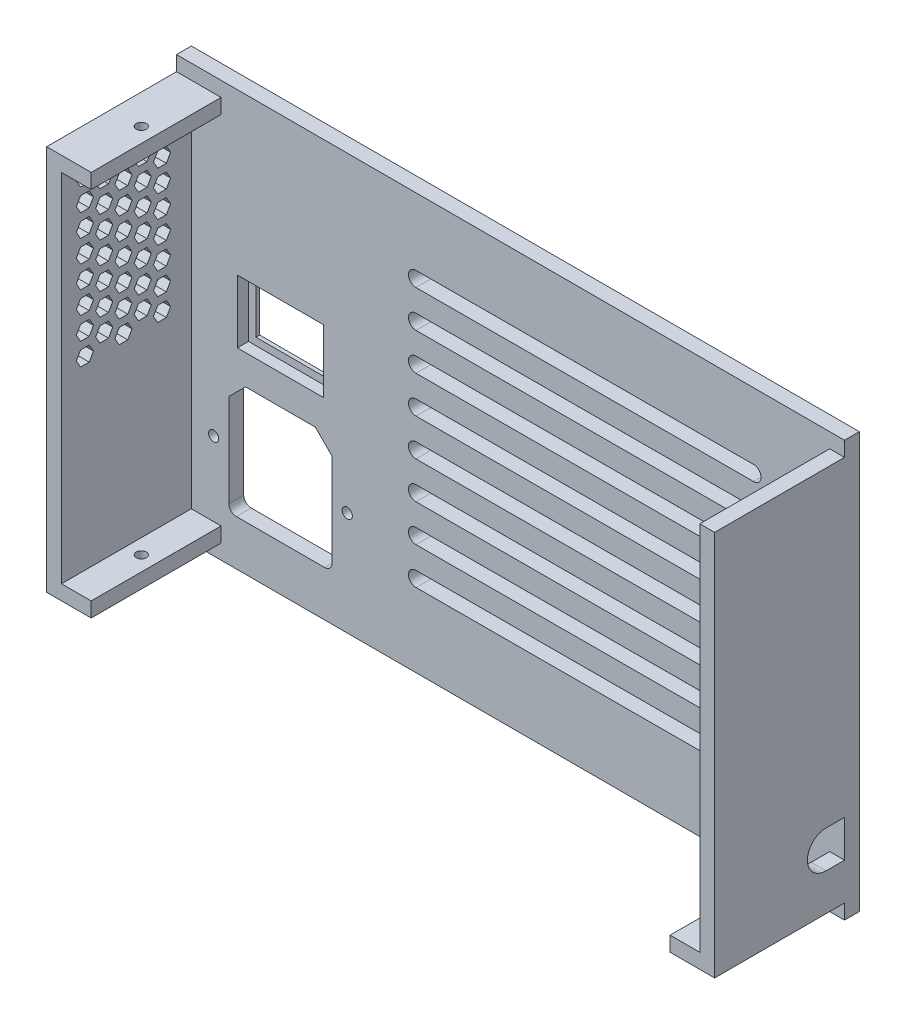
SolidWorks part; units mm, degrees
material "PET"
ref_plane "Přední rovina" through (0, 0, 0) normal (0, 0, 1) x (1, 0, 0)
ref_plane "Horní rovina" through (0, 0, 0) normal (0, 1, 0) x (1, 0, 0)
ref_plane "Pravá rovina" through (0, 0, 0) normal (1, 0, 0) x (0, 0, -1)
sketch "Skica1" plane through (0, 0, 0) normal (0, 0, 1) x (1, 0, 0)
  line L1 (-90, -56) -> (90, -56)
  line L2 (-90, -56) -> (-90, 56)
  line L3 (-90, 56) -> (90, 56)
  line L4 (90, -56) -> (90, 56)
  line L5 (-90, -56) -> (90, 56) construction
  line L6 (-90, 56) -> (90, -56) construction
  point P0 (0, 0)
  dimension "D1" = 112
  dimension "D2" = 180
extrude "Přidat vysunutím1" add sketch "Skica1" along normal blind 4
sketch "Skica2" plane through (0, 0, 4) normal (0, 0, 1) x (1, 0, 0)
  line L0 (-90, 0) -> (90, 0) construction
  line L1 (-90, 56) -> (-90, -56) construction
  line L2 (90, -56) -> (90, 56) construction
  line L3 (90, 56) -> (-90, 56) construction
  line L4 (-90, 52) -> (-86, 52)
  line L5 (-90, 52) -> (-90, -52)
  line L6 (-90, -52) -> (-86, -52)
  line L7 (-86, 52) -> (-86, -52)
  line L8 (-90, 52) -> (-86, -52) construction
  line L9 (-90, -52) -> (-86, 52) construction
  line L10 (-90, -56) -> (90, -56) construction
  line L11 (0, 56) -> (0, -56) construction
  line L12 (90, -52) -> (86, 52) construction
  line L13 (90, 52) -> (86, -52) construction
  line L14 (86, 52) -> (86, -52)
  line L15 (90, -52) -> (86, -52)
  line L16 (90, 52) -> (90, -52)
  line L17 (90, 52) -> (86, 52)
  point P10 (-88, 0)
  point P21 (88, 0)
  dimension "D1" = 4
  dimension "D2" = 4
  dimension "D3" = 4
extrude "Přidat vysunutím2" add sketch "Skica2" along normal blind 35
sketch "Skica3" plane through (0, 0, 4) normal (0, 0, 1) x (1, 0, 0)
  line L5 (-86, 52) -> (-78, 52)
  line L6 (-86, 52) -> (-86, 48)
  line L7 (86, -52) -> (78, -52)
  line L8 (86, -52) -> (86, -48)
  line L9 (86, -48) -> (78, -48)
  line L10 (78, -52) -> (78, -48)
  line L11 (86, -52) -> (78, -48) construction
  line L12 (86, -48) -> (78, -52) construction
  line L13 (-86, -52) -> (-78, -52)
  line L14 (-86, -52) -> (-86, -48)
  line L15 (-86, -48) -> (-78, -48)
  line L16 (-78, -52) -> (-78, -48)
  line L17 (-86, -52) -> (-78, -48) construction
  line L18 (-86, -48) -> (-78, -52) construction
  line L19 (-86, 48) -> (-78, 48)
  line L20 (-78, 52) -> (-78, 48)
  line L21 (-86, 52) -> (-78, 48) construction
  line L22 (-86, 48) -> (-78, 52) construction
  point P4 (-82, 50)
  point P10 (82, -50)
  point P16 (-82, -50)
  dimension "D1" = 4
  dimension "D2" = 8
  dimension "D3" = 4
  dimension "D4" = 8
  dimension "D5" = 4
  dimension "D6" = 8
extrude "Přidat vysunutím3" add sketch "Skica3" along normal up to surface (35 mm away) up to face at (-88, 0, 39)
sketch "Skica5" plane through (0, 52, 0) normal (0, 1, 0) x (1, 0, 0)
  line L0 (-82, -21.5) -> (-78, -21.5) construction
  line L1 (-78, -39) -> (-78, -4) construction
  line L2 (0, 0) -> (0, -47.5141) construction
  line L3 (90, 0) -> (-90, 0) construction
  line L4 (82, -21.5) -> (78, -21.5) construction
  circle A0 centre (-82, -21.5) radius 1.35
  circle A1 centre (82, -21.5) radius 1.35
  dimension "D1" = 2.7
  dimension "D2" = 4
extrude "Odebrat vysunutím2" cut sketch "Skica5" against normal up to surface (104 mm away) up to face at (-84, -52, 21.5)
sketch "Skica8" plane through (86, 0, 0) normal (-1, 0, 0) x (0, 0, 1)
  line L0 (4, 52) -> (4, -48) construction
  line L1 (39, -52) -> (4, -52) construction
  line L2 (9, -42) -> (4, -42)
  line L3 (4, -42) -> (4, -32)
  line L4 (4, -32) -> (9, -32)
  arc A0 (9, -42) -> (9, -32) centre (9, -37) ccw
  dimension "D1" = 10
  dimension "D2" = 15
extrude "Odebrat vysunutím4" cut sketch "Skica8" against normal up to surface (4 mm away) up to face at (90, 0, 11.75)
sketch "Skica9" plane through (0, 0, 4) normal (0, 0, 1) x (1, 0, 0)
  line L0 (20, -34) -> (20, 36) construction
  line L1 (90, 56) -> (-90, 56) construction
  line L3 (-25.4999, 35.8936) -> (65.4999, 36.1064) construction
  line L4 (-25.5046, 37.8936) -> (65.4952, 38.1064)
  line L5 (-25.4952, 33.8936) -> (65.5046, 34.1064)
  line L6 (-25.4999, 25.8936) -> (65.4999, 26.1064) construction
  line L7 (-25.5046, 27.8936) -> (65.4952, 28.1064)
  line L8 (-25.4952, 23.8936) -> (65.5046, 24.1064)
  line L9 (-25.4999, 15.8936) -> (65.4999, 16.1064) construction
  line L10 (-25.5046, 17.8936) -> (65.4952, 18.1064)
  line L11 (-25.4952, 13.8936) -> (65.5046, 14.1064)
  line L12 (-25.4999, 5.8936) -> (65.4999, 6.1064) construction
  line L13 (-25.5046, 7.8936) -> (65.4952, 8.1064)
  line L14 (-25.4952, 3.8936) -> (65.5046, 4.1064)
  line L15 (-25.4999, -4.1064) -> (65.4999, -3.8936) construction
  line L16 (-25.5046, -2.1064) -> (65.4952, -1.8936)
  line L17 (-25.4952, -6.1064) -> (65.5046, -5.8936)
  line L18 (-25.4999, -14.1064) -> (65.4999, -13.8936) construction
  line L19 (-25.5046, -12.1064) -> (65.4952, -11.8936)
  line L20 (-25.4952, -16.1064) -> (65.5046, -15.8936)
  line L21 (-25.4999, -24.1064) -> (65.4999, -23.8936) construction
  line L22 (-25.5046, -22.1064) -> (65.4952, -21.8936)
  line L23 (-25.4952, -26.1064) -> (65.5046, -25.8936)
  line L24 (-25.4999, -34.1064) -> (65.4999, -33.8936) construction
  line L25 (-25.5046, -32.1064) -> (65.4952, -31.8936)
  line L26 (-25.4952, -36.1064) -> (65.5046, -35.8936)
  line L28 (90, -52) -> (90, 52) construction
  arc A0 (-25.5046, 37.8936) -> (-25.4952, 33.8936) centre (-25.4999, 35.8936) ccw
  arc A1 (65.5046, 34.1064) -> (65.4952, 38.1064) centre (65.4999, 36.1064) ccw
  arc A2 (-25.5046, 27.8936) -> (-25.4952, 23.8936) centre (-25.4999, 25.8936) ccw
  arc A3 (65.5046, 24.1064) -> (65.4952, 28.1064) centre (65.4999, 26.1064) ccw
  arc A4 (-25.5046, 17.8936) -> (-25.4952, 13.8936) centre (-25.4999, 15.8936) ccw
  arc A5 (65.5046, 14.1064) -> (65.4952, 18.1064) centre (65.4999, 16.1064) ccw
  arc A6 (-25.5046, 7.8936) -> (-25.4952, 3.8936) centre (-25.4999, 5.8936) ccw
  arc A7 (65.5046, 4.1064) -> (65.4952, 8.1064) centre (65.4999, 6.1064) ccw
  arc A8 (-25.5046, -2.1064) -> (-25.4952, -6.1064) centre (-25.4999, -4.1064) ccw
  arc A9 (65.5046, -5.8936) -> (65.4952, -1.8936) centre (65.4999, -3.8936) ccw
  arc A10 (-25.5046, -12.1064) -> (-25.4952, -16.1064) centre (-25.4999, -14.1064) ccw
  arc A11 (65.5046, -15.8936) -> (65.4952, -11.8936) centre (65.4999, -13.8936) ccw
  arc A12 (-25.5046, -22.1064) -> (-25.4952, -26.1064) centre (-25.4999, -24.1064) ccw
  arc A13 (65.5046, -25.8936) -> (65.4952, -21.8936) centre (65.4999, -23.8936) ccw
  arc A14 (-25.5046, -32.1064) -> (-25.4952, -36.1064) centre (-25.4999, -34.1064) ccw
  arc A15 (65.5046, -35.8936) -> (65.4952, -31.8936) centre (65.4999, -33.8936) ccw
  point P8 (20, 36)
  point P17 (20, 26)
  point P24 (20, 16)
  point P31 (20, 6)
  point P38 (20, -4)
  point P45 (20, -14)
  point P52 (20, -24)
  point P59 (20, -34)
  dimension "D2" = 95
  dimension "D1" = 4
  dimension "D3" = 20
  dimension "D5" = 70
  dimension "D4" = 8
extrude "Odebrat vysunutím5" cut sketch "Skica9" against normal up to surface (4 mm away) up to face at (0, 0, 0)
sketch "Skica12" plane through (-90, 0, 0) normal (-1, 0, 0) x (0, 0, 1)
  line L0 (21.5, 52) -> (21.5, -52) construction
  line L1 (39, 52) -> (4, 52) construction
  line L2 (39, -52) -> (4, -52) construction
  line L3 (11.9737, 33.5) -> (31.0263, 44.5) construction
  line L4 (11.2237, 34.799) -> (30.2763, 45.799)
  line L5 (12.7237, 32.201) -> (31.7763, 43.201)
  line L6 (11.9737, 26.5) -> (31.0263, 37.5) construction
  line L7 (11.2237, 27.799) -> (30.2763, 38.799)
  line L8 (12.7237, 25.201) -> (31.7763, 36.201)
  line L9 (11.9737, 19.5) -> (31.0263, 30.5) construction
  line L10 (11.2237, 20.799) -> (30.2763, 31.799)
  line L11 (12.7237, 18.201) -> (31.7763, 29.201)
  line L12 (11.9737, 12.5) -> (31.0263, 23.5) construction
  line L13 (11.2237, 13.799) -> (30.2763, 24.799)
  line L14 (12.7237, 11.201) -> (31.7763, 22.201)
  line L15 (11.9737, 5.5) -> (31.0263, 16.5) construction
  line L16 (11.2237, 6.799) -> (30.2763, 17.799)
  line L17 (12.7237, 4.201) -> (31.7763, 15.201)
  line L18 (11.9737, -1.5) -> (31.0263, 9.5) construction
  line L19 (11.2237, -0.201) -> (30.2763, 10.799)
  line L20 (12.7237, -2.799) -> (31.7763, 8.201)
  line L21 (-9.8311, 46) -> (42.9995, 46) construction
  line L25 (10.4737, 58.4395) -> (10.4737, -1.4392) construction
  arc A0 (11.2237, 34.799) -> (12.7237, 32.201) centre (11.9737, 33.5) ccw
  arc A1 (31.7763, 43.201) -> (30.2763, 45.799) centre (31.0263, 44.5) ccw
  arc A2 (11.2237, 27.799) -> (12.7237, 25.201) centre (11.9737, 26.5) ccw
  arc A3 (31.7763, 36.201) -> (30.2763, 38.799) centre (31.0263, 37.5) ccw
  arc A4 (11.2237, 20.799) -> (12.7237, 18.201) centre (11.9737, 19.5) ccw
  arc A5 (31.7763, 29.201) -> (30.2763, 31.799) centre (31.0263, 30.5) ccw
  arc A6 (11.2237, 13.799) -> (12.7237, 11.201) centre (11.9737, 12.5) ccw
  arc A7 (31.7763, 22.201) -> (30.2763, 24.799) centre (31.0263, 23.5) ccw
  arc A8 (11.2237, 6.799) -> (12.7237, 4.201) centre (11.9737, 5.5) ccw
  arc A9 (31.7763, 15.201) -> (30.2763, 17.799) centre (31.0263, 16.5) ccw
  arc A10 (11.2237, -0.201) -> (12.7237, -2.799) centre (11.9737, -1.5) ccw
  arc A11 (31.7763, 8.201) -> (30.2763, 10.799) centre (31.0263, 9.5) ccw
  point P8 (21.5, 39)
  point P17 (21.5, 32)
  point P24 (21.5, 25)
  point P31 (21.5, 18)
  point P38 (21.5, 11)
  point P45 (21.5, 4)
  dimension "D2" = 25
  dimension "D4" = 6
  dimension "D1" = 3
  dimension "D3" = 60
  dimension "D5" = 6
sketch "Skica13" plane through (-90, 0, 0) normal (-1, 0, 0) x (0, 0, 1)
  line L0 (39, 52) -> (4, 52) construction
  line L1 (35, 46) -> (8, 46) construction
  line L2 (35, 46) -> (35, 1.7121) construction
  line L3 (35, 1.7121) -> (8, 1.7121) construction
  line L4 (8, 46) -> (8, 1.7121) construction
  line L5 (35, 46) -> (8, 1.7121) construction
  line L6 (35, 1.7121) -> (8, 46) construction
  line L7 (39, 52) -> (39, -52) construction
  line L8 (4, 56) -> (4, 52) construction
  line L9 (32.6906, 44) -> (27.4944, 41) construction
  line L10 (35, 44) -> (33.8453, 46)
  line L11 (33.8453, 46) -> (31.5359, 46)
  line L12 (31.5359, 46) -> (30.3812, 44)
  line L13 (30.3812, 44) -> (31.5359, 42)
  line L14 (31.5359, 42) -> (33.8453, 42)
  line L15 (33.8453, 42) -> (35, 44)
  line L16 (29.8038, 41) -> (28.6491, 43)
  line L17 (28.6491, 43) -> (26.3397, 43)
  line L18 (26.3397, 43) -> (25.185, 41)
  line L19 (25.185, 41) -> (26.3397, 39)
  line L20 (26.3397, 39) -> (28.6491, 39)
  line L21 (28.6491, 39) -> (29.8038, 41)
  line L22 (35, 32) -> (33.8453, 34)
  line L23 (35, 38) -> (33.8453, 40)
  line L24 (33.8453, 40) -> (31.5359, 40)
  line L25 (31.5359, 40) -> (30.3812, 38)
  line L26 (30.3812, 38) -> (31.5359, 36)
  line L27 (31.5359, 36) -> (33.8453, 36)
  line L28 (33.8453, 36) -> (35, 38)
  line L29 (29.8038, 35) -> (28.6491, 37)
  line L30 (28.6491, 37) -> (26.3397, 37)
  line L31 (26.3397, 37) -> (25.185, 35)
  line L32 (25.185, 35) -> (26.3397, 33)
  line L33 (26.3397, 33) -> (28.6491, 33)
  line L34 (28.6491, 33) -> (29.8038, 35)
  line L35 (33.8453, 34) -> (31.5359, 34)
  line L36 (31.5359, 34) -> (30.3812, 32)
  line L37 (30.3812, 32) -> (31.5359, 30)
  line L38 (31.5359, 30) -> (33.8453, 30)
  line L39 (33.8453, 30) -> (35, 32)
  line L40 (35, 26) -> (33.8453, 28)
  line L41 (33.8453, 28) -> (31.5359, 28)
  line L42 (31.5359, 28) -> (30.3812, 26)
  line L43 (30.3812, 26) -> (31.5359, 24)
  line L44 (31.5359, 24) -> (33.8453, 24)
  line L45 (33.8453, 24) -> (35, 26)
  line L46 (29.8038, 29) -> (28.6491, 31)
  line L47 (28.6491, 31) -> (26.3397, 31)
  line L48 (26.3397, 31) -> (25.185, 29)
  line L49 (25.185, 29) -> (26.3397, 27)
  line L50 (26.3397, 27) -> (28.6491, 27)
  line L51 (28.6491, 27) -> (29.8038, 29)
  line L52 (29.8038, 23) -> (28.6491, 25)
  line L53 (28.6491, 25) -> (26.3397, 25)
  line L54 (26.3397, 25) -> (25.185, 23)
  line L55 (25.185, 23) -> (26.3397, 21)
  line L56 (26.3397, 21) -> (28.6491, 21)
  line L57 (28.6491, 21) -> (29.8038, 23)
  line L58 (35, 20) -> (33.8453, 22)
  line L59 (33.8453, 22) -> (31.5359, 22)
  line L60 (31.5359, 22) -> (30.3812, 20)
  line L61 (30.3812, 20) -> (31.5359, 18)
  line L62 (31.5359, 18) -> (33.8453, 18)
  line L63 (33.8453, 18) -> (35, 20)
  line L64 (35, 14) -> (33.8453, 16)
  line L65 (33.8453, 16) -> (31.5359, 16)
  line L66 (31.5359, 16) -> (30.3812, 14)
  line L67 (30.3812, 14) -> (31.5359, 12)
  line L68 (31.5359, 12) -> (33.8453, 12)
  line L69 (33.8453, 12) -> (35, 14)
  line L70 (29.8038, 17) -> (28.6491, 19)
  line L71 (28.6491, 19) -> (26.3397, 19)
  line L72 (26.3397, 19) -> (25.185, 17)
  line L73 (25.185, 17) -> (26.3397, 15)
  line L74 (26.3397, 15) -> (28.6491, 15)
  line L75 (28.6491, 15) -> (29.8038, 17)
  line L76 (29.8038, 11) -> (28.6491, 13)
  line L77 (28.6491, 13) -> (26.3397, 13)
  line L78 (26.3397, 13) -> (25.185, 11)
  line L79 (25.185, 11) -> (26.3397, 9)
  line L80 (26.3397, 9) -> (28.6491, 9)
  line L81 (28.6491, 9) -> (29.8038, 11)
  line L82 (35, 8) -> (33.8453, 10)
  line L83 (33.8453, 10) -> (31.5359, 10)
  line L84 (31.5359, 10) -> (30.3812, 8)
  line L85 (30.3812, 8) -> (31.5359, 6)
  line L86 (31.5359, 6) -> (33.8453, 6)
  line L87 (33.8453, 6) -> (35, 8)
  line L88 (35, 2) -> (33.8453, 4)
  line L89 (33.8453, 4) -> (31.5359, 4)
  line L90 (31.5359, 4) -> (30.3812, 2)
  line L91 (30.3812, 2) -> (31.5359, 0)
  line L92 (31.5359, 0) -> (33.8453, 0)
  line L93 (33.8453, 0) -> (35, 2)
  line L94 (29.8038, 5) -> (28.6491, 7)
  line L95 (28.6491, 7) -> (26.3397, 7)
  line L96 (26.3397, 7) -> (25.185, 5)
  line L97 (25.185, 5) -> (26.3397, 3)
  line L98 (26.3397, 3) -> (28.6491, 3)
  line L99 (28.6491, 3) -> (29.8038, 5)
  line L106 (24.61, 44) -> (23.4553, 46)
  line L107 (23.4553, 46) -> (21.1459, 46)
  line L108 (21.1459, 46) -> (19.9912, 44)
  line L109 (19.9912, 44) -> (21.1459, 42)
  line L110 (21.1459, 42) -> (23.4553, 42)
  line L111 (23.4553, 42) -> (24.61, 44)
  line L112 (19.4138, 41) -> (18.2591, 43)
  line L113 (18.2591, 43) -> (15.9497, 43)
  line L114 (15.9497, 43) -> (14.795, 41)
  line L115 (14.795, 41) -> (15.9497, 39)
  line L116 (15.9497, 39) -> (18.2591, 39)
  line L117 (18.2591, 39) -> (19.4138, 41)
  line L118 (24.61, 38) -> (23.4553, 40)
  line L119 (23.4553, 40) -> (21.1459, 40)
  line L120 (21.1459, 40) -> (19.9912, 38)
  line L121 (19.9912, 38) -> (21.1459, 36)
  line L122 (21.1459, 36) -> (23.4553, 36)
  line L123 (23.4553, 36) -> (24.61, 38)
  line L124 (19.4138, 35) -> (18.2591, 37)
  line L125 (18.2591, 37) -> (15.9497, 37)
  line L126 (15.9497, 37) -> (14.795, 35)
  line L127 (14.795, 35) -> (15.9497, 33)
  line L128 (15.9497, 33) -> (18.2591, 33)
  line L129 (18.2591, 33) -> (19.4138, 35)
  line L130 (24.61, 32) -> (23.4553, 34)
  line L131 (23.4553, 34) -> (21.1459, 34)
  line L132 (21.1459, 34) -> (19.9912, 32)
  line L133 (19.9912, 32) -> (21.1459, 30)
  line L134 (21.1459, 30) -> (23.4553, 30)
  line L135 (23.4553, 30) -> (24.61, 32)
  line L136 (19.4138, 29) -> (18.2591, 31)
  line L137 (18.2591, 31) -> (15.9497, 31)
  line L138 (15.9497, 31) -> (14.795, 29)
  line L139 (14.795, 29) -> (15.9497, 27)
  line L140 (15.9497, 27) -> (18.2591, 27)
  line L141 (18.2591, 27) -> (19.4138, 29)
  line L142 (24.61, 26) -> (23.4553, 28)
  line L143 (23.4553, 28) -> (21.1459, 28)
  line L144 (21.1459, 28) -> (19.9912, 26)
  line L145 (19.9912, 26) -> (21.1459, 24)
  line L146 (21.1459, 24) -> (23.4553, 24)
  line L147 (23.4553, 24) -> (24.61, 26)
  line L148 (19.4138, 23) -> (18.2591, 25)
  line L149 (18.2591, 25) -> (15.9497, 25)
  line L150 (15.9497, 25) -> (14.795, 23)
  line L151 (14.795, 23) -> (15.9497, 21)
  line L152 (15.9497, 21) -> (18.2591, 21)
  line L153 (18.2591, 21) -> (19.4138, 23)
  line L154 (24.61, 20) -> (23.4553, 22)
  line L155 (23.4553, 22) -> (21.1459, 22)
  line L156 (21.1459, 22) -> (19.9912, 20)
  line L157 (19.9912, 20) -> (21.1459, 18)
  line L158 (21.1459, 18) -> (23.4553, 18)
  line L159 (23.4553, 18) -> (24.61, 20)
  line L160 (19.4138, 17) -> (18.2591, 19)
  line L161 (18.2591, 19) -> (15.9497, 19)
  line L162 (15.9497, 19) -> (14.795, 17)
  line L163 (14.795, 17) -> (15.9497, 15)
  line L164 (15.9497, 15) -> (18.2591, 15)
  line L165 (18.2591, 15) -> (19.4138, 17)
  line L166 (24.61, 14) -> (23.4553, 16)
  line L167 (23.4553, 16) -> (21.1459, 16)
  line L168 (21.1459, 16) -> (19.9912, 14)
  line L169 (19.9912, 14) -> (21.1459, 12)
  line L170 (21.1459, 12) -> (23.4553, 12)
  line L171 (23.4553, 12) -> (24.61, 14)
  line L172 (19.4138, 11) -> (18.2591, 13)
  line L173 (18.2591, 13) -> (15.9497, 13)
  line L174 (15.9497, 13) -> (14.795, 11)
  line L175 (14.795, 11) -> (15.9497, 9)
  line L176 (15.9497, 9) -> (18.2591, 9)
  line L177 (18.2591, 9) -> (19.4138, 11)
  line L178 (24.61, 8) -> (23.4553, 10)
  line L179 (23.4553, 10) -> (21.1459, 10)
  line L180 (21.1459, 10) -> (19.9912, 8)
  line L181 (19.9912, 8) -> (21.1459, 6)
  line L182 (21.1459, 6) -> (23.4553, 6)
  line L183 (23.4553, 6) -> (24.61, 8)
  line L184 (19.4138, 5) -> (18.2591, 7)
  line L185 (18.2591, 7) -> (15.9497, 7)
  line L186 (15.9497, 7) -> (14.795, 5)
  line L187 (14.795, 5) -> (15.9497, 3)
  line L188 (15.9497, 3) -> (18.2591, 3)
  line L189 (18.2591, 3) -> (19.4138, 5)
  line L190 (24.61, 2) -> (23.4553, 4)
  line L191 (23.4553, 4) -> (21.1459, 4)
  line L192 (21.1459, 4) -> (19.9912, 2)
  line L193 (19.9912, 2) -> (21.1459, 0)
  line L194 (21.1459, 0) -> (23.4553, 0)
  line L195 (23.4553, 0) -> (24.61, 2)
  line L202 (14.22, 44) -> (13.0653, 46)
  line L203 (13.0653, 46) -> (10.7559, 46)
  line L204 (10.7559, 46) -> (9.6012, 44)
  line L205 (9.6012, 44) -> (10.7559, 42)
  line L206 (10.7559, 42) -> (13.0653, 42)
  line L207 (13.0653, 42) -> (14.22, 44)
  line L214 (14.22, 38) -> (13.0653, 40)
  line L215 (13.0653, 40) -> (10.7559, 40)
  line L216 (10.7559, 40) -> (9.6012, 38)
  line L217 (9.6012, 38) -> (10.7559, 36)
  line L218 (10.7559, 36) -> (13.0653, 36)
  line L219 (13.0653, 36) -> (14.22, 38)
  line L226 (14.22, 32) -> (13.0653, 34)
  line L227 (13.0653, 34) -> (10.7559, 34)
  line L228 (10.7559, 34) -> (9.6012, 32)
  line L229 (9.6012, 32) -> (10.7559, 30)
  line L230 (10.7559, 30) -> (13.0653, 30)
  line L231 (13.0653, 30) -> (14.22, 32)
  line L238 (14.22, 26) -> (13.0653, 28)
  line L239 (13.0653, 28) -> (10.7559, 28)
  line L240 (10.7559, 28) -> (9.6012, 26)
  line L241 (9.6012, 26) -> (10.7559, 24)
  line L242 (10.7559, 24) -> (13.0653, 24)
  line L243 (13.0653, 24) -> (14.22, 26)
  line L250 (14.22, 20) -> (13.0653, 22)
  line L251 (13.0653, 22) -> (10.7559, 22)
  line L252 (10.7559, 22) -> (9.6012, 20)
  line L253 (9.6012, 20) -> (10.7559, 18)
  line L254 (10.7559, 18) -> (13.0653, 18)
  line L255 (13.0653, 18) -> (14.22, 20)
  line L262 (14.22, 14) -> (13.0653, 16)
  line L263 (13.0653, 16) -> (10.7559, 16)
  line L264 (10.7559, 16) -> (9.6012, 14)
  line L265 (9.6012, 14) -> (10.7559, 12)
  line L266 (10.7559, 12) -> (13.0653, 12)
  line L267 (13.0653, 12) -> (14.22, 14)
  line L274 (14.22, 8) -> (13.0653, 10)
  line L275 (13.0653, 10) -> (10.7559, 10)
  line L276 (10.7559, 10) -> (9.6012, 8)
  line L277 (9.6012, 8) -> (10.7559, 6)
  line L278 (10.7559, 6) -> (13.0653, 6)
  line L279 (13.0653, 6) -> (14.22, 8)
  line L286 (14.22, 2) -> (13.0653, 4)
  line L287 (13.0653, 4) -> (10.7559, 4)
  line L288 (10.7559, 4) -> (9.6012, 2)
  line L289 (9.6012, 2) -> (10.7559, 0)
  line L290 (10.7559, 0) -> (13.0653, 0)
  line L291 (13.0653, 0) -> (14.22, 2)
  line L298 (9.0238, 41) -> (7.8691, 43) [skipped]
  line L299 (7.8691, 43) -> (5.5597, 43) [skipped]
  line L300 (5.5597, 43) -> (4.405, 41) [skipped]
  line L301 (4.405, 41) -> (5.5597, 39) [skipped]
  line L302 (5.5597, 39) -> (7.8691, 39) [skipped]
  line L303 (7.8691, 39) -> (9.0238, 41) [skipped]
  line L304 (9.0238, 35) -> (7.8691, 37) [skipped]
  line L305 (7.8691, 37) -> (5.5597, 37) [skipped]
  line L306 (5.5597, 37) -> (4.405, 35) [skipped]
  line L307 (4.405, 35) -> (5.5597, 33) [skipped]
  line L308 (5.5597, 33) -> (7.8691, 33) [skipped]
  line L309 (7.8691, 33) -> (9.0238, 35) [skipped]
  line L310 (9.0238, 29) -> (7.8691, 31) [skipped]
  line L311 (7.8691, 31) -> (5.5597, 31) [skipped]
  line L312 (5.5597, 31) -> (4.405, 29) [skipped]
  line L313 (4.405, 29) -> (5.5597, 27) [skipped]
  line L314 (5.5597, 27) -> (7.8691, 27) [skipped]
  line L315 (7.8691, 27) -> (9.0238, 29) [skipped]
  line L316 (9.0238, 23) -> (7.8691, 25) [skipped]
  line L317 (7.8691, 25) -> (5.5597, 25) [skipped]
  line L318 (5.5597, 25) -> (4.405, 23) [skipped]
  line L319 (4.405, 23) -> (5.5597, 21) [skipped]
  line L320 (5.5597, 21) -> (7.8691, 21) [skipped]
  line L321 (7.8691, 21) -> (9.0238, 23) [skipped]
  line L322 (9.0238, 17) -> (7.8691, 19) [skipped]
  line L323 (7.8691, 19) -> (5.5597, 19) [skipped]
  line L324 (5.5597, 19) -> (4.405, 17) [skipped]
  line L325 (4.405, 17) -> (5.5597, 15) [skipped]
  line L326 (5.5597, 15) -> (7.8691, 15) [skipped]
  line L327 (7.8691, 15) -> (9.0238, 17) [skipped]
  line L328 (9.0238, 11) -> (7.8691, 13) [skipped]
  line L329 (7.8691, 13) -> (5.5597, 13) [skipped]
  line L330 (5.5597, 13) -> (4.405, 11) [skipped]
  line L331 (4.405, 11) -> (5.5597, 9) [skipped]
  line L332 (5.5597, 9) -> (7.8691, 9) [skipped]
  line L333 (7.8691, 9) -> (9.0238, 11) [skipped]
  line L334 (9.0238, 5) -> (7.8691, 7) [skipped]
  line L335 (7.8691, 7) -> (5.5597, 7) [skipped]
  line L336 (5.5597, 7) -> (4.405, 5) [skipped]
  line L337 (4.405, 5) -> (5.5597, 3) [skipped]
  line L338 (5.5597, 3) -> (7.8691, 3) [skipped]
  line L339 (7.8691, 3) -> (9.0238, 5) [skipped]
  line L352 (29.8038, -1) -> (28.6491, 1) [skipped]
  line L353 (28.6491, 1) -> (26.3397, 1) [skipped]
  line L354 (26.3397, 1) -> (25.185, -1) [skipped]
  line L355 (25.185, -1) -> (26.3397, -3) [skipped]
  line L356 (26.3397, -3) -> (28.6491, -3) [skipped]
  line L357 (28.6491, -3) -> (29.8038, -1) [skipped]
  circle A0 centre (32.6906, 44) radius 2 construction
  circle A1 centre (27.4944, 41) radius 2 construction
  circle A2 centre (32.6906, 38) radius 2 construction
  circle A3 centre (27.4944, 35) radius 2 construction
  point P4 (21.5, 23.8561)
  dimension "D1" = 6
  dimension "D2" = 4
  dimension "D3" = 4
  dimension "D4" = 4
  dimension "D5" = 4
  dimension "D6" = 2
  dimension "D7" = 30
  dimension "D8" = 4
  dimension "D9" = 2
  dimension "D10" = 2
  dimension "D11" = 4
  dimension "D12" = 2
  dimension "D13" = 2
  dimension "D15" = 3
  dimension "D14" = 4
extrude "Odebrat vysunutím9" cut sketch "Skica13" against normal up to surface (4 mm away) up to face at (-86, 0, 21.5)
sketch "Skica15" plane through (0, 0, 4) normal (0, 0, 1) x (1, 0, 0)
  line L0 (-80, -28) -> (-44, -28) construction
  line L1 (-90, 52) -> (-90, -52) construction
  line L2 (-90, -56) -> (90, -56) construction
  line L4 (-75.9, -43.75) -> (-48.1, -43.75)
  line L5 (-75.9, -43.75) -> (-75.9, -12.25)
  line L6 (-75.9, -12.25) -> (-48.1, -12.25)
  line L7 (-48.1, -43.75) -> (-48.1, -12.25)
  line L8 (-75.9, -43.75) -> (-48.1, -12.25) construction
  line L9 (-75.9, -12.25) -> (-48.1, -43.75) construction
  circle A0 centre (-80, -28) radius 1.375
  circle A1 centre (-44, -28) radius 1.375
  point P8 (-62, -28)
  dimension "D2" = 2.75
  dimension "D3" = 2.75
  dimension "D1" = 36
  dimension "D4" = 10
  dimension "D5" = 28
  dimension "D6" = 27.8
  dimension "D7" = 31.5
extrude "Odebrat vysunutím10" cut sketch "Skica15" against normal up to surface (4 mm away) up to face at (20, 36, 0)
chamfer "Zkosení1" distance 4.5 angle 45 2 edges at (-75.9, -12.25, 2) (-48.1, -12.25, 2)
fillet "Zaoblit1" radius 2 2 edges at (-48.1, -43.75, 2) (-75.9, -43.75, 2)
sketch "Skica18" plane through (0, 0, 4) normal (0, 0, 1) x (1, 0, 0)
  line L0 (-62, -43.75) -> (-62, 56) construction
  line L1 (-73.9, -43.75) -> (-50.1, -43.75) construction
  line L2 (90, 56) -> (-90, 56) construction
  line L3 (-52.6, -12.25) -> (-71.4, -12.25) construction
  line L4 (-71.6, 10.75) -> (-52.4, 10.75)
  line L5 (-71.6, 10.75) -> (-71.6, -2.25)
  line L6 (-71.6, -2.25) -> (-52.4, -2.25)
  line L7 (-52.4, 10.75) -> (-52.4, -2.25)
  line L8 (-71.6, 10.75) -> (-52.4, -2.25) construction
  line L9 (-71.6, -2.25) -> (-52.4, 10.75) construction
  point P6 (-62, 4.25)
  dimension "D1" = 13
  dimension "D2" = 19.2
  dimension "D3" = 10
extrude "Odebrat vysunutím11" cut sketch "Skica18" against normal up to surface (4 mm away) up to face at (-81.375, -28, 0)
sketch "Skica19" plane through (0, 0, 4) normal (0, 0, 1) x (1, 0, 0)
  line L0 (-71.6, 4.25) -> (-52.4, 4.25) construction
  line L1 (-71.6, 10.75) -> (-71.6, -2.25) construction
  line L2 (-52.4, -2.25) -> (-52.4, 10.75) construction
  line L3 (-52.4, 10.75) -> (-71.6, 10.75) construction
  line L4 (-50.4, -4.25) -> (-73.6, -4.25)
  line L5 (-50.4, -4.25) -> (-50.4, 12.75)
  line L6 (-50.4, 12.75) -> (-73.6, 12.75)
  line L7 (-73.6, -4.25) -> (-73.6, 12.75)
  line L8 (-50.4, -4.25) -> (-73.6, 12.75) construction
  line L9 (-50.4, 12.75) -> (-73.6, -4.25) construction
  point P6 (-62, 4.25)
  dimension "D1" = 2
  dimension "D2" = 2
extrude "Odebrat vysunutím12" cut sketch "Skica19" against normal blind 3
